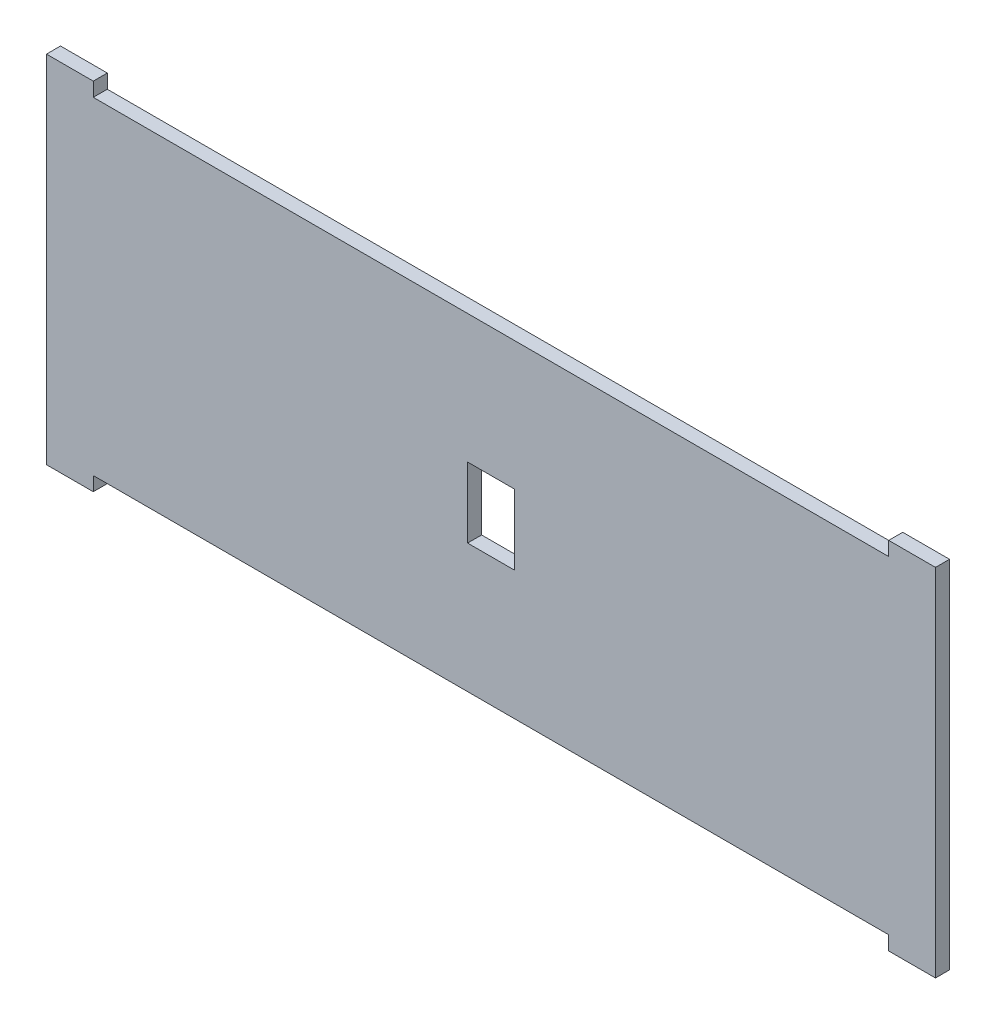
SolidWorks part; units mm, degrees
ref_plane "Plano frontal" through (0, 0, 0) normal (0, 0, 1) x (1, 0, 0)
ref_plane "Plano superior" through (0, 0, 0) normal (0, 1, 0) x (1, 0, 0)
ref_plane "Plano direito" through (0, 0, 0) normal (1, 0, 0) x (0, 0, -1)
sketch "Esboço1" plane through (0, 0, 0) normal (0, 0, 1) x (1, 0, 0)
  line L1 (95, -35) -> (-95, -35)
  line L2 (95, -35) -> (95, 35)
  line L3 (95, 35) -> (-95, 35)
  line L4 (-95, -35) -> (-95, 35)
  line L5 (95, -35) -> (-95, 35) construction
  line L6 (95, 35) -> (-95, -35) construction
  line L7 (-95, -35) -> (-85, -35)
  line L8 (-95, -35) -> (-95, -38)
  line L9 (-95, -38) -> (-85, -38)
  line L10 (-85, -35) -> (-85, -38)
  line L11 (95, -35) -> (85, -35)
  line L12 (95, -35) -> (95, -38)
  line L13 (95, -38) -> (85, -38)
  line L14 (85, -35) -> (85, -38)
  line L15 (95, 35) -> (85, 35)
  line L16 (95, 35) -> (95, 38)
  line L17 (95, 38) -> (85, 38)
  line L18 (85, 35) -> (85, 38)
  line L19 (-95, 35) -> (-85, 35)
  line L20 (-95, 35) -> (-95, 38)
  line L21 (-95, 38) -> (-85, 38)
  line L22 (-85, 35) -> (-85, 38)
  point P0 (0, 0)
  dimension "D1" = 70
  dimension "D2" = 190
  dimension "D3" = 10
  dimension "D4" = 10
  dimension "D5" = 10
  dimension "D6" = 10
  dimension "D7" = 3
  dimension "D8" = 3
  dimension "D9" = 3
  dimension "D10" = 3
extrude "Ressalto-extrusão1" add sketch "Esboço1" along normal blind 3 contours L10 L1 L8 L9 | L3 L22 L21 L20 | L4 L1 L2 L3 | L18 L3 L16 L17 | L1 L14 L13 L12
sketch "Esboço2" plane through (0, 0, 3) normal (0, 0, 1) x (1, 0, 0)
  line L1 (5, -7.5) -> (-5, -7.5)
  line L2 (5, -7.5) -> (5, 7.5)
  line L3 (5, 7.5) -> (-5, 7.5)
  line L4 (-5, -7.5) -> (-5, 7.5)
  line L5 (5, -7.5) -> (-5, 7.5) construction
  line L6 (5, 7.5) -> (-5, -7.5) construction
  point P0 (0, 0)
  dimension "D1" = 15
  dimension "D2" = 10
extrude "Corte-extrusão1" cut sketch "Esboço2" against normal blind 10
